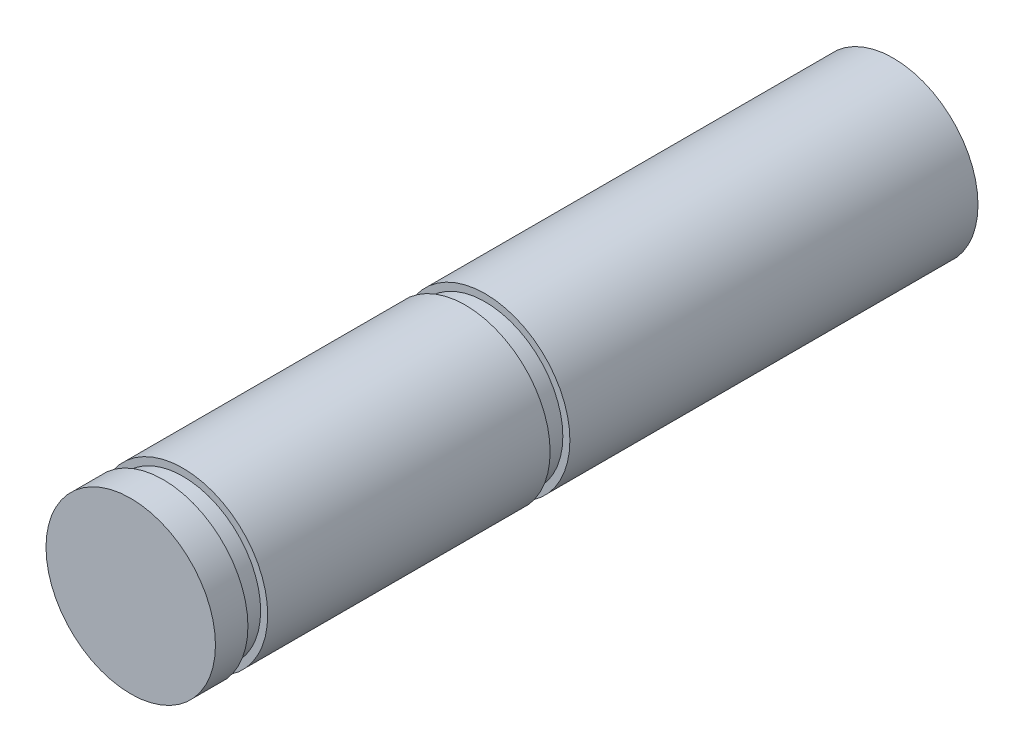
SolidWorks part; units mm, degrees
ref_plane "정면" through (0, 0, 0) normal (0, 0, 1) x (1, 0, 0)
ref_plane "윗면" through (0, 0, 0) normal (0, 1, 0) x (1, 0, 0)
ref_plane "우측면" through (0, 0, 0) normal (1, 0, 0) x (0, 0, -1)
sketch "스케치1" plane through (0, 0, 0) normal (0, 0, 1) x (1, 0, 0)
  circle A0 centre (0, 0) radius 3
  dimension "D1" = 6
extrude "보스-돌출1" add sketch "스케치1" along normal blind 27
ref_plane "평면1" through (0, 0, 25.5) normal (0, 0, 1) x (1, 0, 0)
sketch "스케치2" plane through (0, 0, 25.5) normal (0, 0, 1) x (1, 0, 0)
  circle A0 centre (0, 0) radius 2.75
  circle A1 centre (0, 0) radius 3
  circle A2 centre (0, 0) radius 3
  dimension "D1" = 0
  dimension "D2" = 0.25
extrude "컷-돌출1" cut sketch "스케치2" against normal blind 0.35 and the other way blind 0.35
ref_plane "평면2" through (0, 0, 15.15) normal (0, 0, 1) x (1, 0, 0)
sketch "스케치3" plane through (0, 0, 15.15) normal (0, 0, 1) x (1, 0, 0)
  circle A0 centre (0, 0) radius 2.75
  circle A1 centre (0, 0) radius 3
  circle A2 centre (0, 0) radius 3
  dimension "D1" = 0
  dimension "D2" = 0.25
extrude "컷-돌출2" cut sketch "스케치3" against normal blind 0.7
